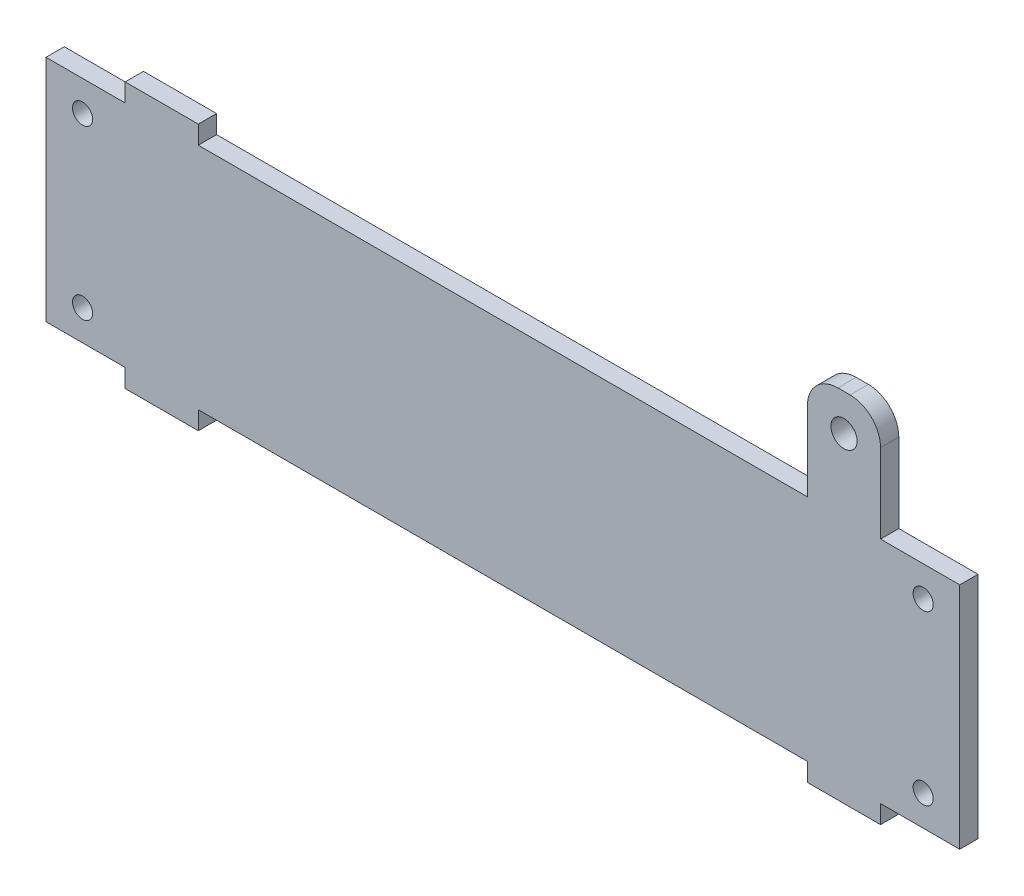
SolidWorks part; units mm, degrees
material "Thornel Mat VMA"
ref_plane "前视基准面" through (0, 0, 0) normal (0, 0, 1) x (1, 0, 0)
ref_plane "上视基准面" through (0, 0, 0) normal (0, 1, 0) x (1, 0, 0)
ref_plane "右视基准面" through (0, 0, 0) normal (1, 0, 0) x (0, 0, -1)
sketch "草图1" plane through (0, 0, 0) normal (0, 0, 1) x (1, 0, 0)
  line L0 (75, 0) -> (75, 37.6) construction
  line L1 (0, 0) -> (13, 0)
  line L2 (0, 0) -> (0, 37.6)
  line L3 (0, 37.6) -> (13, 37.6)
  line L4 (150, 0) -> (150, 37.6)
  line L5 (0, 18.8) -> (150, 18.8) construction
  line L6 (25, 37.6) -> (125, 37.6)
  line L8 (13, 37.6) -> (13, 40.6)
  line L9 (13, 40.6) -> (25, 40.6)
  line L10 (25, 37.6) -> (25, 40.6)
  line L11 (125, 37.6) -> (125, 40.6)
  line L13 (137, 37.6) -> (137, 40.6)
  line L14 (137, 0) -> (137, -3)
  line L15 (137, -3) -> (125, -3)
  line L16 (125, 0) -> (125, -3)
  line L17 (25, 0) -> (25, -3)
  line L18 (13, -3) -> (25, -3)
  line L19 (13, 0) -> (13, -3)
  line L20 (25, 0) -> (125, 0)
  line L21 (137, 0) -> (150, 0)
  line L22 (137, 37.6) -> (150, 37.6)
  line L23 (125, 40.6) -> (125, 55.6)
  line L24 (125, 55.6) -> (137, 55.6)
  line L25 (137, 55.6) -> (137, 40.6)
  line L26 (131, 55.6) -> (131, 43.6) construction
  circle A0 centre (131, 49.6) radius 2.15
  circle A1 centre (6, 32.6) radius 1.65
  circle A2 centre (6, 5) radius 1.65
  circle A3 centre (144, 32.6) radius 1.65
  circle A4 centre (144, 5) radius 1.65
  dimension "D8" = 4.3
  dimension "D9" = 6
  dimension "D10" = 3.3
  dimension "D11" = 27.6
  dimension "D12" = 6
  dimension "D1" = 37.6
  dimension "D2" = 150
  dimension "D3" = 3
  dimension "D4" = 12
  dimension "D5" = 100
  dimension "D6" = 75
  dimension "D7" = 18
extrude "凸台-拉伸1" add sketch "草图1" along normal blind 3
fillet "圆角1" radius 5 2 edges at (137, 55.6, 1.5) (125, 55.6, 1.5)
